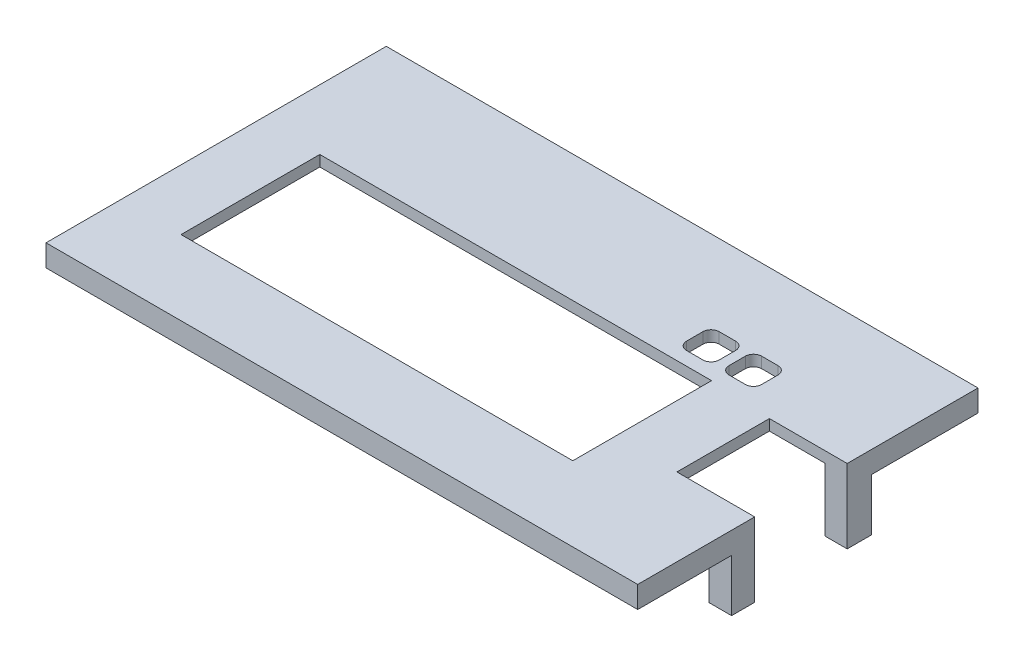
SolidWorks part; units mm, degrees
ref_plane "正面" through (0, 0, 0) normal (0, 0, 1) x (1, 0, 0)
ref_plane "平面" through (0, 0, 0) normal (0, 1, 0) x (1, 0, 0)
ref_plane "右側面" through (0, 0, 0) normal (1, 0, 0) x (0, 0, -1)
sketch "arduino" plane through (0, 0, 0) normal (0, 1, 0) x (1, 0, 0)
  line L1 (0, 0) -> (68.58, 0)
  line L2 (0, 0) -> (0, 53.34)
  line L3 (0, 53.34) -> (68.58, 53.34)
  line L4 (68.58, 0) -> (68.58, 53.34)
  line L6 (-6.46, 38.12) -> (9.84, 38.12) construction
  line L7 (-0.5, 53.44) -> (68.68, 53.44) construction
  line L8 (-0.5, 53.44) -> (-0.5, -0.1) construction
  line L9 (-0.5, -0.1) -> (68.68, -0.1) construction
  line L10 (68.68, 53.44) -> (68.68, -0.1) construction
  line L11 (-6.46, 44.12) -> (9.84, 44.12)
  line L12 (-6.46, 44.12) -> (-6.46, 32.12)
  line L13 (-6.46, 32.12) -> (9.84, 32.12)
  line L14 (9.84, 44.12) -> (9.84, 32.12)
  line L15 (-1.96, 12.72) -> (11.74, 12.72)
  line L16 (-1.96, 12.72) -> (-1.96, 3.72)
  line L17 (-1.96, 3.72) -> (11.74, 3.72)
  line L18 (11.74, 12.72) -> (11.74, 3.72)
  line L19 (1.69, 44.12) -> (1.69, 32.12) construction
  line L20 (-1.96, 8.22) -> (11.74, 8.22) construction
  line L21 (4.89, 12.72) -> (4.89, 3.72) construction
  line L22 (34.29, 53.34) -> (34.29, 0) construction
  line L23 (-2.06, 12.82) -> (11.84, 12.82) construction
  line L24 (-2.06, 12.82) -> (-2.06, 3.62) construction
  line L25 (-2.06, 3.62) -> (11.84, 3.62) construction
  line L26 (11.84, 12.82) -> (11.84, 3.62) construction
  line L27 (-6.56, 44.22) -> (9.94, 44.22) construction
  line L28 (-6.56, 44.22) -> (-6.56, 32.02) construction
  line L29 (-6.56, 32.02) -> (9.94, 32.02) construction
  line L30 (9.94, 44.22) -> (9.94, 32.02) construction
  line L31 (0, 26.67) -> (68.58, 26.67) construction
  dimension "D1" = 68.58
  dimension "D2" = 53.34
  dimension "D3" = 0.5
  dimension "D4" = 0.1
  dimension "D5" = 0.1
  dimension "D6" = 0.1
  dimension "D7" = 12
  dimension "D8" = 16.3
  dimension "D9" = 11.45
  dimension "D10" = 32.6
  dimension "D11" = 9
  dimension "D12" = 13.7
  dimension "D13" = 29.4
  dimension "D14" = 18.45
  dimension "D15" = 0.1
  dimension "D16" = 0.1
  dimension "D17" = 0.1
  dimension "D18" = 0.1
  dimension "D19" = 0.1
  dimension "D20" = 0.1
  dimension "D21" = 0.1
  dimension "D22" = 0.1
sketch "lcd" plane through (0, 0, 0) normal (0, 1, 0) x (1, 0, 0)
  line L0 (-31.77, 22.32) -> (68.84, 22.32) construction
  line L1 (53.23, 37.32) -> (-31.77, 37.32)
  line L2 (53.23, 37.32) -> (53.23, 7.32)
  line L3 (53.23, 7.32) -> (-31.77, 7.32)
  line L4 (-31.77, 37.32) -> (-31.77, 7.32)
  line L6 (26.34, 37.32) -> (26.34, 7.32) construction
  line L7 (-25.57, 35.02) -> (45.73, 35.02)
  line L8 (0, 26.67) -> (68.58, 26.67) construction
  line L9 (34.29, 53.34) -> (34.29, 0) construction
  line L10 (-25.57, 35.02) -> (-25.57, 9.72)
  line L11 (-25.57, 9.72) -> (45.73, 9.72)
  line L12 (45.73, 35.02) -> (45.73, 9.72)
  line L13 (68.58, 0) -> (68.58, 53.34) construction
  dimension "D1" = 2.4
  dimension "D2" = 30
  dimension "D3" = 85
  dimension "D4" = 25.3
  dimension "D5" = 4.35
  dimension "D6" = 7.95
  dimension "D7" = 71.3
  dimension "D8" = 7.5
  dimension "D9" = 15.35
sketch "frame" plane through (0, 0, 0) normal (0, 1, 0) x (1, 0, 0)
  line L0 (-31.77, 37.32) -> (-31.77, 7.32) construction
  line L1 (72.78, -4.1) -> (-35.97, -4.1)
  line L2 (72.78, -4.1) -> (72.78, 58.44)
  line L3 (72.78, 58.44) -> (-35.97, 58.44)
  line L4 (-35.97, -4.1) -> (-35.97, 58.44)
  line L6 (-0.5, -0.1) -> (68.68, -0.1) construction
  line L7 (-0.5, 53.44) -> (68.68, 53.44) construction
  line L8 (-35.97, 27.17) -> (58.78, 27.17) construction
  line L9 (14.08, 56.44) -> (14.08, -3.1) construction
  line L10 (68.58, 0) -> (68.58, 53.34) construction
  line L11 (-31.97, 54.44) -> (68.78, 54.44)
  line L12 (-31.97, 54.44) -> (-31.97, -0.1)
  line L13 (-31.97, -0.1) -> (68.78, -0.1)
  line L14 (68.78, 54.44) -> (68.78, -0.1)
  dimension "D1" = 4.2
  dimension "D2" = 4.2
  dimension "D3" = 4
  dimension "D4" = 5
  dimension "D5" = 4
  dimension "D6" = 4
  dimension "D7" = 4
  dimension "D8" = 4
sketch "lid" plane through (0, 0, 0) normal (0, 1, 0) x (1, 0, 0)
  line L0 (72.78, -4.1) -> (72.78, 58.44) construction
  line L1 (-35.97, 58.44) -> (72.78, 58.44)
  line L2 (-35.97, 58.44) -> (-35.97, -4.1)
  line L3 (-35.97, -4.1) -> (72.78, -4.1)
  line L4 (72.78, 58.44) -> (72.78, -4.1)
  line L5 (72.78, -4.1) -> (-35.97, -4.1) construction
  line L6 (72.78, 58.44) -> (-35.97, 58.44) construction
  line L7 (-37.62, 26.67) -> (65.78, 26.67) construction
  line L8 (14.08, 56.44) -> (14.08, -3.1) construction
  line L13 (-35.97, -4.1) -> (-35.97, 58.44) construction
  dimension "D3" = 0
  dimension "D4" = 0
extrude "ﾎﾞｽ - 押し出し1" add sketch "lid" along normal blind 2
sketch "ｽｹｯﾁ8" plane through (0, 2, 0) normal (0, 1, 0) x (1, 0, 0)
  line L0 (-25.57, 35.02) -> (45.73, 35.02) construction
  line L1 (-24.87, 35.12) -> (47.13, 35.12)
  line L2 (-24.87, 35.12) -> (-24.87, 9.62)
  line L3 (-24.87, 9.62) -> (47.13, 9.62)
  line L4 (47.13, 35.12) -> (47.13, 9.62)
  line L5 (45.73, 35.02) -> (45.73, 9.72) construction
  line L6 (-25.57, 9.72) -> (45.73, 9.72) construction
  line L7 (-25.57, 35.02) -> (-25.57, 9.72) construction
  dimension "D1" = 0.1
  dimension "D2" = 1.4
  dimension "D3" = 0.1
  dimension "D4" = 0.7
extrude "ｶｯﾄ - 押し出し1" cut sketch "ｽｹｯﾁ8" against normal up to next
sketch "ｽｹｯﾁ12" plane through (0, 2, 0) normal (0, 1, 0) x (1, 0, 0)
  line L1 (72.78, 58.44) -> (-35.97, 58.44) construction
  line L2 (-35.97, 58.44) -> (-35.97, -4.1) construction
  line L6 (-35.97, -4.1) -> (72.78, -4.1) construction
  circle A0 centre (-32.52, 53.99) radius 1.55
  circle A1 centre (-32.52, 0.35) radius 1.55
  dimension "D1" = 3.1
  dimension "D2" = 2.9
  dimension "D3" = 1.9
  dimension "D4" = 3.1
  dimension "D5" = 2.9
  dimension "D6" = 1.9
sketch "ｽｹｯﾁ14" plane through (0, 0, 0) normal (0, 1, 0) x (1, 0, 0)
  line L0 (0, 26.67) -> (68.58, 26.67) construction
  line L2 (34.29, 53.34) -> (34.29, 0) construction
  circle A0 centre (41.54, 37.62) radius 1.7
  circle A1 centre (49.34, 37.62) radius 1.7
  dimension "D1" = 3.4
  dimension "D2" = 3.4
  dimension "D3" = 10.95
  dimension "D4" = 10.95
  dimension "D5" = 15.05
  dimension "D6" = 7.25
sketch "ｽｹｯﾁ15" plane through (0, 2, 0) normal (0, 1, 0) x (1, 0, 0)
  line L0 (41.54, 43.62) -> (41.54, 37.62) construction
  line L1 (38.54, 43.62) -> (44.54, 43.62)
  line L2 (38.54, 43.62) -> (38.54, 37.62)
  line L3 (38.54, 37.62) -> (44.54, 37.62)
  line L4 (44.54, 43.62) -> (44.54, 37.62)
  line L5 (46.34, 43.62) -> (52.34, 43.62)
  line L6 (46.34, 43.62) -> (46.34, 37.62)
  line L7 (46.34, 37.62) -> (52.34, 37.62)
  line L8 (52.34, 43.62) -> (52.34, 37.62)
  line L9 (49.34, 43.62) -> (49.34, 37.62) construction
  line L10 (38.54, 40.62) -> (44.54, 40.62) construction
  line L11 (46.34, 40.62) -> (52.34, 40.62) construction
  dimension "D1" = 6
  dimension "D2" = 6
  dimension "D3" = 6
  dimension "D4" = 6
  dimension "D5" = 3
  dimension "D6" = 3
extrude "ｶｯﾄ - 押し出し3" cut sketch "ｽｹｯﾁ15" against normal up to next
fillet "ﾌｨﾚｯﾄ1" radius 1.5 8 edges at (44.54, 1, -43.62) (52.34, 1, -43.62) (52.34, 1, -37.62) (44.54, 1, -37.62) (46.34, 1, -43.62) (46.34, 1, -37.62) (38.54, 1, -37.62) (38.54, 1, -43.62)
sketch "ｽｹｯﾁ16" plane through (0, 0, 0) normal (0, -1, 0) x (1, 0, 0)
  line L1 (-35.97, 4.1) -> (72.78, 4.1)
  line L2 (-35.97, 4.1) -> (-35.97, -58.44)
  line L3 (-35.97, -58.44) -> (72.78, -58.44)
  line L4 (72.78, 4.1) -> (72.78, -58.44)
  line L5 (-33.97, 2.1) -> (70.78, 2.1)
  line L6 (-33.97, 2.1) -> (-33.97, -56.44)
  line L7 (-33.97, -56.44) -> (70.78, -56.44)
  line L8 (70.78, 2.1) -> (70.78, -56.44)
  dimension "D1" = 2
  dimension "D2" = 2
  dimension "D3" = 2
  dimension "D4" = 2
extrude "ﾎﾞｽ - 押し出し2" add sketch "ｽｹｯﾁ16" along normal blind 2
sketch "ｽｹｯﾁ17" plane through (0, 2, 0) normal (0, 1, 0) x (1, 0, 0)
  line L0 (72.78, -4.1) -> (72.78, 58.44) construction
  line L1 (72.78, 17.4) -> (58.48, 17.4)
  line L2 (72.78, 17.4) -> (72.78, 34.4)
  line L3 (72.78, 34.4) -> (58.48, 34.4)
  line L4 (58.48, 17.4) -> (58.48, 34.4)
  line L6 (-35.97, -4.1) -> (72.78, -4.1) construction
  dimension "D1" = 21.5
  dimension "D2" = 17
  dimension "D3" = 14.3
extrude "ｶｯﾄ - 押し出し4" cut sketch "ｽｹｯﾁ17" against normal blind 4
sketch "ｽｹｯﾁ18" plane through (0, 0, 0) normal (0, -1, 0) x (1, 0, 0)
  line L0 (72.78, -34.4) -> (70.78, -34.4) construction
  line L1 (68.68, -38.9) -> (72.78, -38.9)
  line L2 (68.68, -38.9) -> (68.68, -34.4)
  line L3 (68.68, -34.4) -> (72.78, -34.4)
  line L4 (72.78, -38.9) -> (72.78, -34.4)
  line L5 (68.68, -53.44) -> (68.68, 0.1) construction
  line L6 (72.78, -58.44) -> (72.78, -34.4) construction
  line L7 (72.78, 4.1) -> (72.78, -58.44) construction
  line L8 (68.6106, -17.4) -> (72.78, -17.4)
  line L9 (68.6106, -17.4) -> (68.6106, -13.15)
  line L10 (68.6106, -13.15) -> (72.78, -13.15)
  line L11 (72.78, -17.4) -> (72.78, -13.15)
  line L12 (70.78, -17.4) -> (72.78, -17.4) construction
  point P16 (71.78, -17.4)
  dimension "D1" = 4.5
  dimension "D2" = 0
  dimension "D3" = 0
  dimension "D4" = 0
  dimension "D5" = 4.25
  dimension "D6" = 0
  dimension "D7" = 0
extrude "ﾎﾞｽ - 押し出し3" add sketch "ｽｹｯﾁ18" along normal blind 11.6
